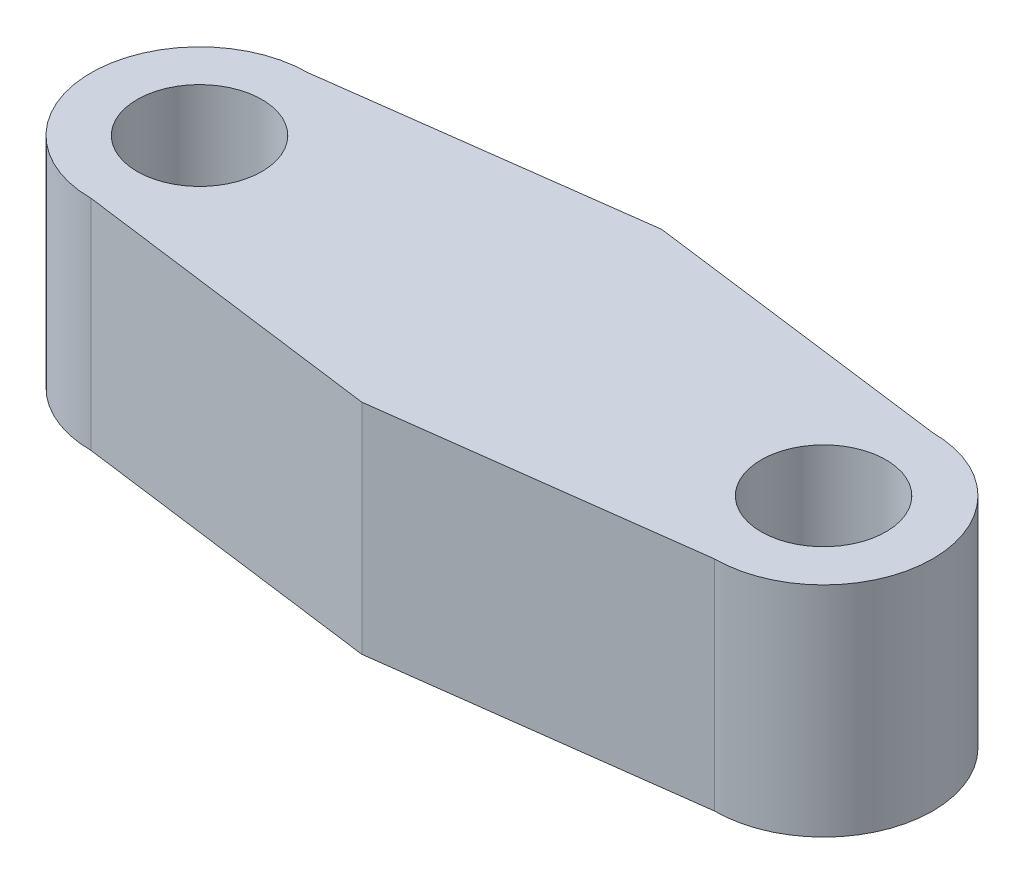
SolidWorks part; units mm, degrees
ref_plane "Front Plane" through (0, 0, 0) normal (0, 0, 1) x (1, 0, 0)
ref_plane "Top Plane" through (0, 0, 0) normal (0, 1, 0) x (1, 0, 0)
ref_plane "Right Plane" through (0, 0, 0) normal (1, 0, 0) x (0, 0, -1)
sketch "Sketch1" plane through (0, 0, 0) normal (0, 1, 0) x (1, 0, 0)
  line L0 (0, 0) -> (5, 0)
  line L1 (0, 0) -> (-5, 0)
  line L6 (0, -2.4) -> (5, -1.7497)
  line L7 (0, -2.4) -> (-5, -1.7407)
  line L8 (0, 2.4) -> (-5, 1.7407)
  line L9 (0, 2.4) -> (5, 1.7497)
  circle A1 centre (5, 0) radius 1
  circle A2 centre (-5, 0) radius 1
  arc A6 (0.6139, 2.3202) -> (-0.6221, 2.318) centre (0, 0) ccw
  arc A7 (5, -1.7497) -> (5, 1.7497) centre (5, 0) ccw
  arc A8 (-5, 1.7407) -> (-5, -1.7407) centre (-5, 0) ccw
  arc A9 (-0.6221, -2.318) -> (0.6139, -2.3202) centre (0, 0) ccw
  dimension "D1" = 5
  dimension "D2" = 5
extrude "Boss-Extrude1" add sketch "Sketch1" along normal blind 3.5
sketch "Sketch4" plane through (0, 3.5, 0) normal (0, 1, 0) x (1, 0, 0)
  circle A0 centre (0, 0) radius 2.4
